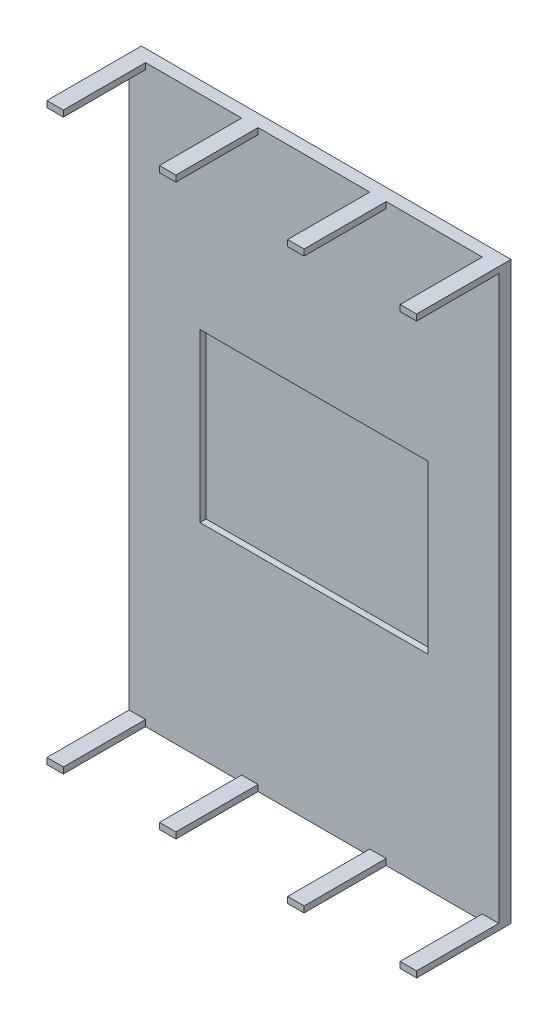
SolidWorks part; units mm, degrees
ref_plane "Front Plane" through (0, 0, 0) normal (1, 0, 0) x (0, 1, 0)
ref_plane "Top Plane" through (0, 0, 0) normal (0, 0, 1) x (0, 1, 0)
ref_plane "Right Plane" through (0, 0, 0) normal (0, 1, 0) x (-1, 0, 0)
sketch "Sketch1" plane through (0, 0, 0) normal (0, 0, 1) x (0, 1, 0)
  line L0 (-70, -45) -> (70, 45) construction
  line L1 (70, -45) -> (-70, -45)
  line L2 (70, -45) -> (70, 45)
  line L3 (70, 45) -> (-70, 45)
  line L4 (-70, -45) -> (-70, 45)
  line L5 (-70, 45) -> (70, -45) construction
  point P4 (0, 0)
  dimension "D1" = 90
  dimension "D2" = 140
extrude "Boss-Extrude1" add sketch "Sketch1" along normal blind 3
sketch "Sketch2" plane through (0, 0, 3) normal (0, 0, 1) x (1, 0, 0)
  line L0 (0, 70) -> (0, -70) construction
  line L1 (-45, 70) -> (-41, 70)
  line L2 (-45, 70) -> (-45, 68.5)
  line L3 (-45, 68.5) -> (-41, 68.5)
  line L4 (-41, 70) -> (-41, 68.5)
  line L5 (45, 70) -> (-45, 70) construction
  line L6 (-45, -70) -> (45, -70) construction
  line L7 (-45, 0) -> (45, 0) construction
  line L8 (-45, 70) -> (-45, -70) construction
  line L9 (45, -70) -> (45, 70) construction
  line L10 (45, 68.5) -> (41, 68.5)
  line L11 (41, 70) -> (41, 68.5)
  line L12 (45, 70) -> (41, 70)
  line L13 (45, 70) -> (45, 68.5)
  line L14 (45, -70) -> (45, -68.5)
  line L15 (45, -70) -> (41, -70)
  line L16 (41, -70) -> (41, -68.5)
  line L17 (45, -68.5) -> (41, -68.5)
  line L18 (-45, -68.5) -> (-41, -68.5)
  line L19 (-41, -70) -> (-41, -68.5)
  line L20 (-45, -70) -> (-41, -70)
  line L21 (-45, -70) -> (-45, -68.5)
  line L22 (-17.6, 70) -> (-13.6, 70)
  line L23 (-17.6, 70) -> (-17.6, 68.5)
  line L24 (-17.6, 68.5) -> (-13.6, 68.5)
  line L25 (-13.6, 70) -> (-13.6, 68.5)
  line L26 (17.6, 70) -> (17.6, 68.5)
  line L27 (17.6, 68.5) -> (13.6, 68.5)
  line L28 (13.6, 70) -> (13.6, 68.5)
  line L29 (17.6, 70) -> (13.6, 70)
  line L30 (17.6, -70) -> (13.6, -70)
  line L31 (13.6, -70) -> (13.6, -68.5)
  line L32 (17.6, -68.5) -> (13.6, -68.5)
  line L33 (17.6, -70) -> (17.6, -68.5)
  line L34 (-17.6, -70) -> (-17.6, -68.5)
  line L35 (-17.6, -68.5) -> (-13.6, -68.5)
  line L36 (-13.6, -70) -> (-13.6, -68.5)
  line L37 (-17.6, -70) -> (-13.6, -70)
  line M15 (45, 70) -> (-45, 70)
  line M16 (-45, 70) -> (-45, -70)
  line M17 (-45, -70) -> (45, -70)
  line M18 (45, -70) -> (45, 70)
  dimension "D1" = 1.5
  dimension "D2" = 4
  dimension "D3" = 23.4
extrude "Boss-Extrude2" add sketch "Sketch2" along normal blind 20 contours L4 L3 M15 M16 | L25 L23 L24 M15 | L28 L27 L26 M15 | L11 L10 M15 M18 | L19 L18 M17 M16 | L36 L35 L34 M17 | L32 L31 L30 L33 | L15 L16 L17 L14
sketch "Sketch4" plane through (0, 0, 3) normal (0, 0, 1) x (1, 0, 0)
  line L0 (-27.75, -20.35) -> (27.75, -20.35)
  line L1 (-27.75, -20.35) -> (-27.75, 20.35)
  line L2 (27.75, -20.35) -> (27.75, 20.35)
  line L3 (-27.75, 20.35) -> (27.75, 20.35)
  line L4 (-27.75, -20.35) -> (27.75, 20.35) construction
  line L5 (27.75, -20.35) -> (-27.75, 20.35) construction
  point P1 (0, 0)
  dimension "D1" = 55.5
  dimension "D2" = 40.7
extrude "Cut-Extrude1" cut sketch "Sketch4" against normal blind 1.5
